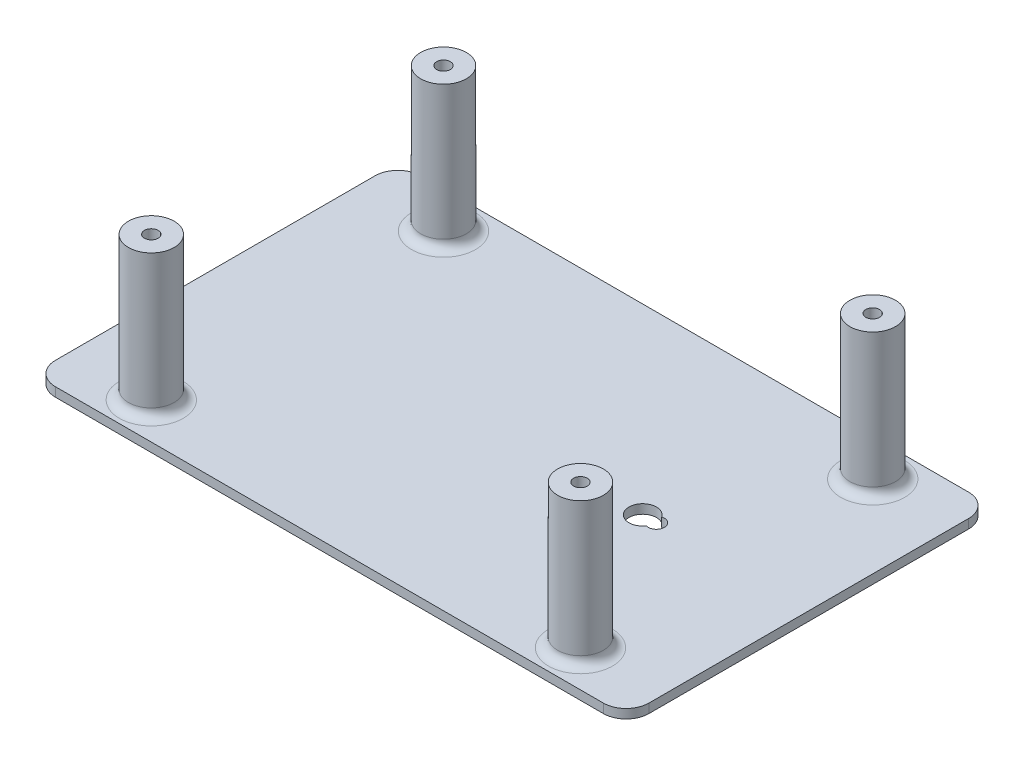
SolidWorks part; units mm, degrees
ref_plane "Спереди" through (0, 0, 0) normal (0, 0, 1) x (1, 0, 0)
ref_plane "Сверху" through (0, 0, 0) normal (0, 1, 0) x (1, 0, 0)
ref_plane "Справа" through (0, 0, 0) normal (1, 0, 0) x (0, 0, -1)
sketch "Эскиз1" plane through (0, 0, 0) normal (0, 1, 0) x (1, 0, 0)
  line L0 (-1000, 0) -> (49000, 0) construction
  line L1 (0, -1000) -> (0, 49000) construction
  line L2 (65, -1000) -> (65, 49000) construction
  line L3 (-65, -1000) -> (-65, 49000) construction
  line L4 (-1000, -40) -> (49000, -40) construction
  line L5 (-1000, 40) -> (49000, 40) construction
  line L6 (-60, 40) -> (60, 40)
  line L7 (65, 35) -> (65, -35)
  line L8 (60, -40) -> (-60, -40)
  line L9 (-65, -35) -> (-65, 35)
  arc A0 (60, 40) -> (65, 35) centre (60, 35) cw
  arc A1 (65, -35) -> (60, -40) centre (60, -35) cw
  arc A2 (-60, -40) -> (-65, -35) centre (-60, -35) cw
  arc A3 (-60, 40) -> (-65, 35) centre (-60, 35) ccw
  point P19 (65, 40)
  point P22 (65, -40)
  point P25 (-65, -40)
  point P28 (-65, 40)
extrude "Бобышка-Вытянуть1" add sketch "Эскиз1" along normal blind 2
sketch "Эскиз2" plane through (0, 2, 0) normal (0, 1, 0) x (1, 0, 0)
  line L0 (-1000, 0) -> (49000, 0) construction
  line L1 (0, -1000) -> (0, 49000) construction
  line L2 (47, -1000) -> (47, 49000) construction
  line L3 (-47, -1000) -> (-47, 49000) construction
  line L4 (-1000, -32) -> (49000, -32) construction
  line L5 (-1000, 32) -> (49000, 32) construction
  circle A0 centre (-47, 32) radius 3.25
  circle A1 centre (47, 32) radius 3.25
  circle A2 centre (-47, -32) radius 3.25
  circle A3 centre (47, -32) radius 3.25
extrude "Вырез-Вытянуть1" cut sketch "Эскиз2" against normal blind 2
sketch "Эскиз5" plane through (0, 2, 0) normal (0, 1, 0) x (1, 0, 0)
  circle A0 centre (-47, 32) radius 3.25
  circle A1 centre (-47, -32) radius 3.25
  circle A2 centre (47, 32) radius 3.25
  circle A3 centre (47, -32) radius 3.25
  circle A4 centre (-47, 32) radius 5
  circle A5 centre (47, 32) radius 5
  circle A6 centre (47, -32) radius 5
  circle A7 centre (-47, -32) radius 5
extrude "Бобышка-Вытянуть2" add sketch "Эскиз5" along normal blind 31.4
fillet "Скругление1" radius 2 4 edges at (-47, 2, 27) (47, 2, 27) (47, 2, -37) (-47, 2, -37)
sketch "Эскиз6" plane through (0, 33.4, 0) normal (0, 1, 0) x (1, 0, 0)
  circle A0 centre (-47, 32) radius 4.0981
  circle A1 centre (-47, 32) radius 1.5
  circle A2 centre (47, 32) radius 4.3023
  circle A3 centre (47, 32) radius 1.5
  circle A4 centre (47, -32) radius 4.2111
  circle A5 centre (47, -32) radius 1.5
  circle A6 centre (-47, -32) radius 4.1152
  circle A7 centre (-47, -32) radius 1.5
extrude "Бобышка-Вытянуть3" add sketch "Эскиз6" against normal blind 15
fillet "Скругление2" radius 2 4 edges at (47, 0, 35.25) (-47, 0, 35.25) (-47, 0, -28.75) (47, 0, -28.75)
sketch "Эскиз7" plane through (0, 0, 0) normal (0, -1, 0) x (1, 0, 0)
  line L0 (-1000, 0) -> (49000, 0) construction
  line L1 (0, -1000) -> (0, 49000) construction
  line L2 (28.6224, -1008.3644) -> (28.6224, 48991.6356) construction
  arc A0 (31.112, 1.6739) -> (31.112, -1.6739) centre (28.6224, 0) ccw
  arc A1 (31.112, -1.6739) -> (31.112, 1.6739) centre (31.6224, 0) ccw
extrude "Вырез-Вытянуть2" cut sketch "Эскиз7" against normal blind 15
